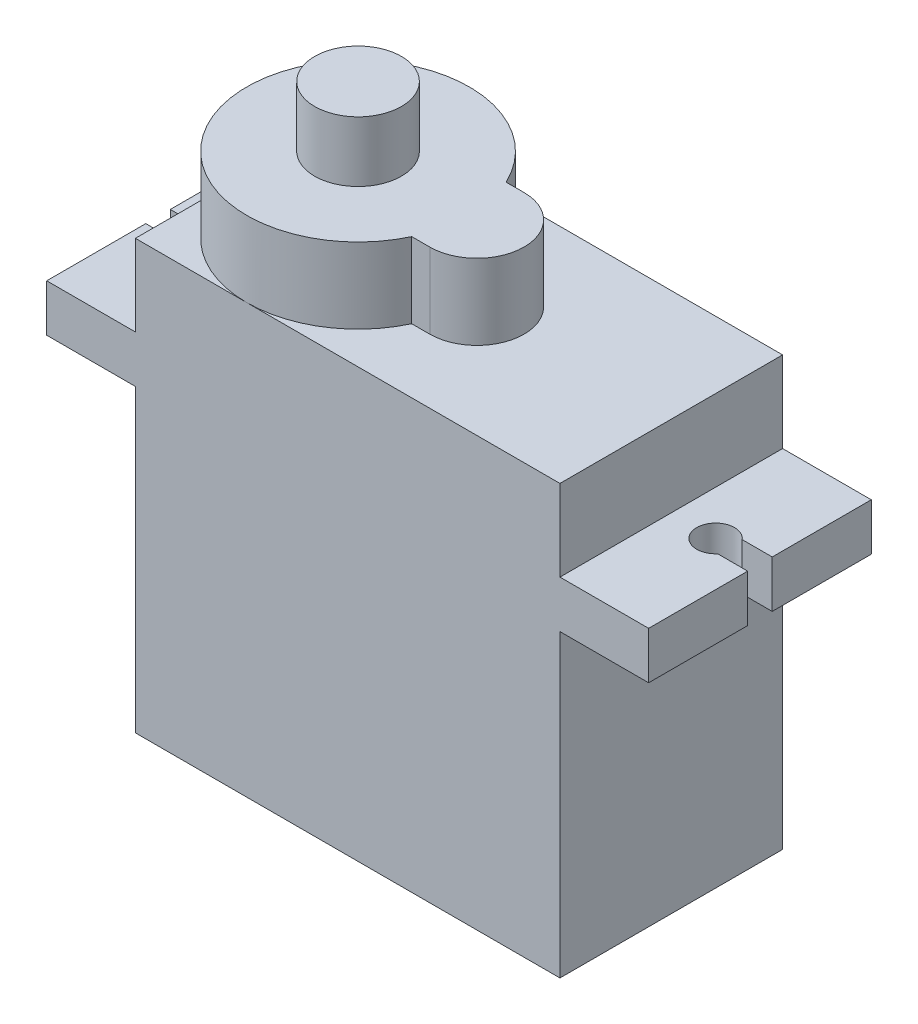
SolidWorks part; units mm, degrees
ref_plane "Ön Düzlem" through (0, 0, 0) normal (0, 0, 1) x (1, 0, 0)
ref_plane "Üst Düzlem" through (0, 0, 0) normal (0, 1, 0) x (1, 0, 0)
ref_plane "Sağ Düzlem" through (0, 0, 0) normal (1, 0, 0) x (0, 0, -1)
sketch "Sketch1" plane through (0, 0, 0) normal (0, 0, 1) x (1, 0, 0)
  line L1 (0, 0) -> (22.5, 0)
  line L2 (0, 0) -> (0, 15.9)
  line L3 (0, 22.7) -> (22.5, 22.7)
  line L4 (22.5, 0) -> (22.5, 15.9)
  line L5 (-4.7, 15.9) -> (0, 15.9)
  line L6 (-4.7, 18.4) -> (0, 18.4)
  line L7 (-4.7, 15.9) -> (-4.7, 18.4)
  line L8 (27.2, 15.9) -> (27.2, 18.4)
  line L9 (22.5, 15.9) -> (27.2, 15.9)
  line L10 (-4.7, 15.9) -> (27.2, 15.9) construction
  line L11 (22.5, 18.4) -> (27.2, 18.4)
  line L12 (-4.7, 18.4) -> (27.2, 18.4) construction
  line L13 (22.5, 18.4) -> (22.5, 22.7)
  line L14 (0, 18.4) -> (0, 22.7)
  dimension "D1" = 22.5
  dimension "D2" = 22.7
  dimension "D3" = 15.9
  dimension "D4" = 31.9
  dimension "D5" = 2.5
extrude "Boss-Extrude1" add sketch "Sketch1" along normal blind 11.8
sketch "Sketch2" plane through (0, 22.7, 0) normal (0, 1, 0) x (1, 0, 0)
  line L0 (0, -5.9) -> (5.9, -5.9) construction
  line L1 (0, -11.8) -> (0, 0) construction
  line L2 (5.9, -5.9) -> (14.7, -5.9) construction
  line L3 (12.2, -3.4) -> (11.2442, -3.4)
  line L4 (12.2, -8.4) -> (11.2442, -8.4)
  arc A0 (11.2442, -3.4) -> (11.2442, -8.4) centre (5.9, -5.9) ccw
  arc A3 (12.2, -8.4) -> (12.2, -3.4) centre (12.2, -5.9) ccw
  dimension "D2" = 8.8
  dimension "D3" = 2.5
  dimension "D1" = 5.9
extrude "Boss-Extrude2" add sketch "Sketch2" along normal blind 4
sketch "Sketch3" plane through (0, 26.7, 0) normal (0, 1, 0) x (1, 0, 0)
  circle A0 centre (5.9, -5.9) radius 2.3
  dimension "D1" = 4.6
extrude "Cut-Extrude1" cut sketch "Sketch3" against normal blind 4
sketch "Sketch4" plane through (0, 18.4, 0) normal (0, 1, 0) x (1, 0, 0)
  line L0 (-2.35, -5.9) -> (-2.35, 0) construction
  line L1 (0, 0) -> (-4.7, 0) construction
  line L2 (-2.35, -5.9) -> (-4.7, -5.9) construction
  line L3 (-4.7, -11.8) -> (-4.7, 0) construction
  line L4 (-4.7, -5.25) -> (-4.7, -6.55)
  line L5 (-4.7, -6.55) -> (-3.1099, -6.55)
  line L6 (-4.7, -5.25) -> (-3.1099, -5.25)
  arc A0 (-3.1099, -6.55) -> (-3.1099, -5.25) centre (-2.35, -5.9) ccw
  point P11 (-4.7, -5.9)
  dimension "D1" = 2
  dimension "D2" = 1.3
extrude "Cut-Extrude2" cut sketch "Sketch4" against normal blind 4
ref_plane "Plane1" through (11.25, 0, 0) normal (1, 0, 0) x (0, 0, -1)
mirror "Mirror1" about plane through (11.25, 0, 0) normal (1, 0, 0) of "Cut-Extrude2"
sketch "Sketch5" plane through (0, 26.7, 0) normal (0, 1, 0) x (1, 0, 0)
  circle A0 centre (5.9, -5.9) radius 2.3
extrude "Boss-Extrude3" add sketch "Sketch5" along normal blind 3.2 separate body
